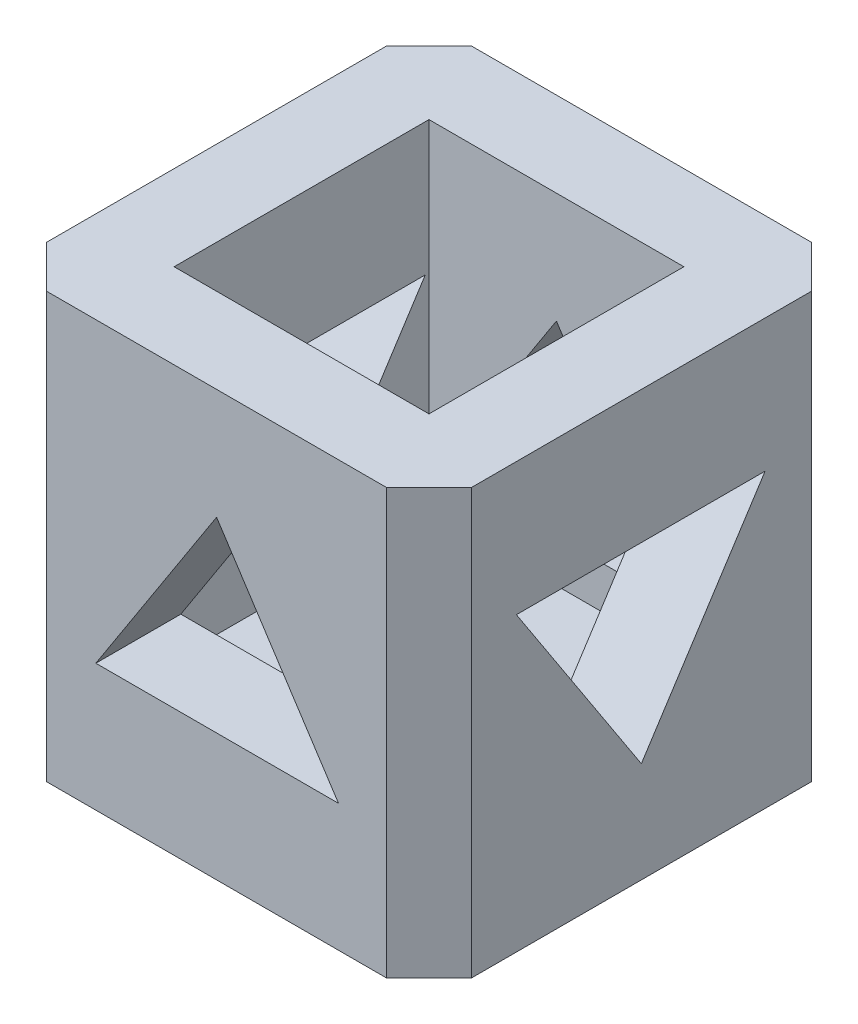
SolidWorks part; units mm, degrees
ref_plane "Plan de face" through (0, 0, 0) normal (0, 0, 1) x (1, 0, 0)
ref_plane "Plan de dessus" through (0, 0, 0) normal (0, 1, 0) x (1, 0, 0)
ref_plane "Plan de droite" through (0, 0, 0) normal (1, 0, 0) x (0, 0, -1)
sketch "Esquisse1" plane through (0, 0, 0) normal (0, 1, 0) x (1, 0, 0)
  line L0 (-10, -10) -> (-10, 10)
  line L1 (-55, 0) -> (55, 0) construction
  line L2 (-10, 10) -> (10, 10)
  line L3 (0, -55) -> (0, 55) construction
  line L4 (10, -10) -> (10, 10)
  line L5 (-10, -10) -> (10, -10)
  point P0 (0, -10)
  point P8 (0, 10)
  point P10 (10, 0)
  point P11 (-10, 0)
  dimension "D1" = 10
  dimension "D2" = 10
extrude "Boss.-Extru.1" add sketch "Esquisse1" along normal blind 4
sketch "Esquisse4" plane through (0, 4, 0) normal (0, 1, 0) x (1, 0, 0)
  line L1 (-10, 10) -> (10, 10)
  line L2 (-10, 10) -> (-10, -10)
  line L3 (-10, -10) -> (10, -10)
  line L4 (10, 10) -> (10, -10)
  line L5 (-6, 6) -> (6, 6)
  line L6 (-6, 6) -> (-6, -6)
  line L7 (-6, -6) -> (6, -6)
  line L8 (6, 6) -> (6, -6)
  dimension "D1" = 4
  dimension "D2" = 12
  dimension "D3" = 12
  dimension "D4" = 4
extrude "Boss.-Extru.2" add sketch "Esquisse4" along normal blind 16
sketch "Esquisse5" plane through (0, 0, 10) normal (0, 0, 1) x (1, 0, 0)
  line L0 (0, 14.7867) -> (-5.685, 5.9914)
  line L1 (0, -11) -> (0, 11) construction
  line L2 (-5.685, 5.9914) -> (5.7397, 5.9914)
  line L3 (5.7397, 5.9914) -> (0, 14.7867)
extrude "Enlèv. mat.-Extru.2" cut sketch "Esquisse5" against normal blind 25 contours L0 L2 L3
sketch "Esquisse6" plane through (10, 0, 0) normal (1, 0, 0) x (0, 0, -1)
  line L0 (-0.0023, 4.7392) -> (5.825, 13.7548)
  line L1 (5.825, 13.7548) -> (-5.8857, 13.7548)
  line L2 (-5.8857, 13.7548) -> (-0.0023, 4.7392)
extrude "Enlèv. mat.-Extru.3" cut sketch "Esquisse6" against normal blind 25
chamfer "Chanfrein1" distance 2 angle 45 4 edges at (10, 10, -10) (10, 10, 10) (-10, 10, 10) (-10, 10, -10)
